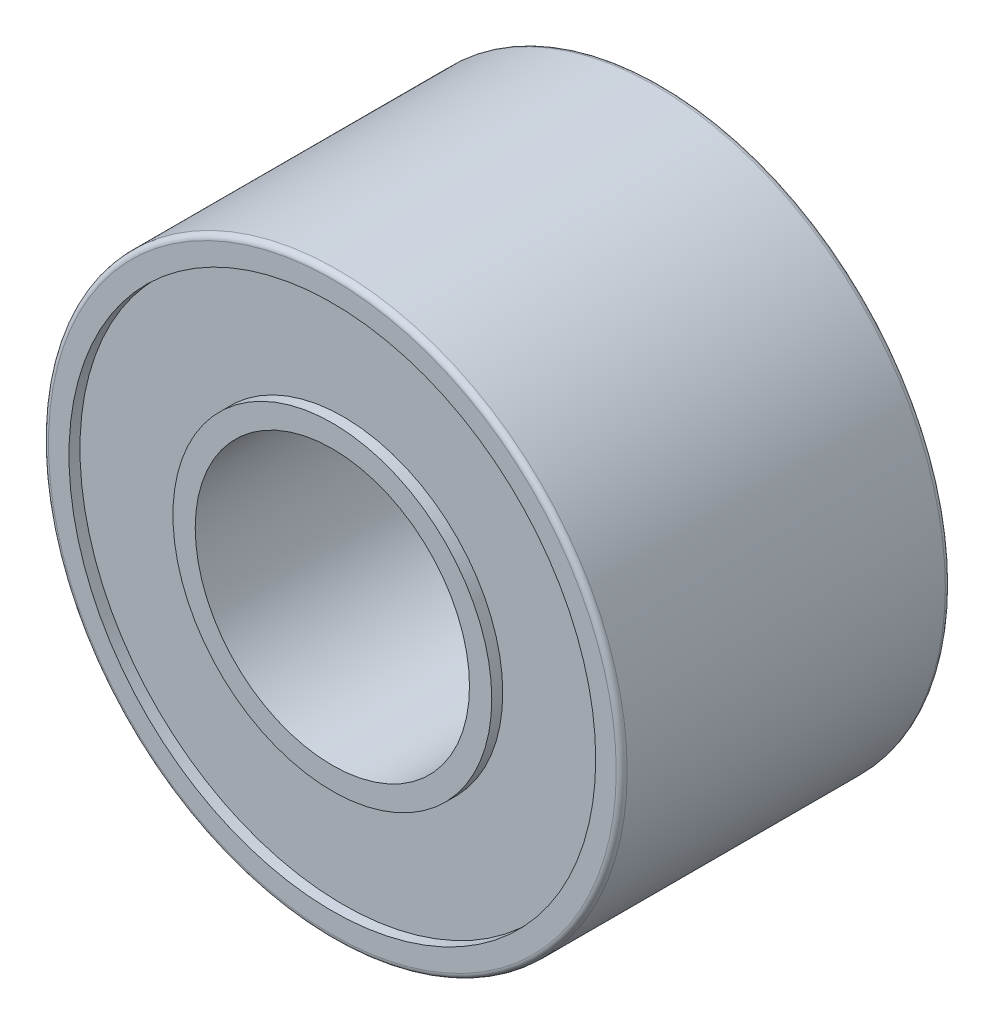
SolidWorks part; units mm, degrees
material "201 Annealed Stainless Steel (SS)"
ref_plane "Plan de face" through (0, 0, 0) normal (0, 0, 1) x (1, 0, 0)
ref_plane "Plan de dessus" through (0, 0, 0) normal (0, 1, 0) x (1, 0, 0)
ref_plane "Plan de droite" through (0, 0, 0) normal (1, 0, 0) x (0, 0, -1)
sketch "Sketch1" plane through (0, 0, 0) normal (0, 0, 1) x (1, 0, 0)
  circle A0 centre (0, 0) radius 10.55
  circle A1 centre (0, 0) radius 5
  dimension "D1" = 21.1
  dimension "D2" = 10
extrude "Boss-Extrude1" add sketch "Sketch1" along normal mid plane 12
fillet "Fillet1" radius 0.2 2 edges at (10.55, 0, -6) (10.55, 0, 6)
sketch "Sketch3" plane through (0, 0, 6) normal (0, 0, 1) x (1, 0, 0)
  circle A0 centre (0, 0) radius 5.8129
  circle A1 centre (0, 0) radius 9.6023
extrude "Cut-Extrude1" cut sketch "Sketch3" against normal blind 0.4
mirror "Mirror1" about plane through (0, 0, 0) normal (0, 0, 1) of "Cut-Extrude1"
